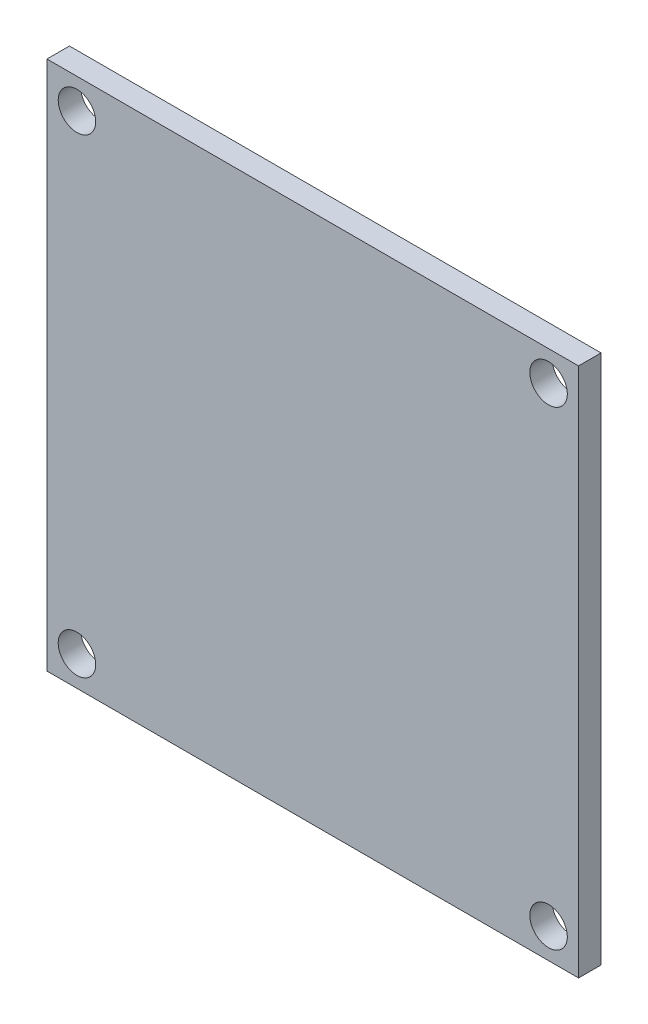
SolidWorks part; units mm, degrees
ref_plane "前视基准面" through (0, 0, 0) normal (0, 0, 1) x (1, 0, 0)
ref_plane "上视基准面" through (0, 0, 0) normal (0, 1, 0) x (1, 0, 0)
ref_plane "右视基准面" through (0, 0, 0) normal (1, 0, 0) x (0, 0, -1)
other "Configuration Table"
sketch "草图1" plane through (0, 0, 0) normal (0, 0, 1) x (1, 0, 0)
  line L1 (-35.45, 35.35) -> (35.45, 35.35)
  line L2 (-35.45, 35.35) -> (-35.45, -35.35)
  line L3 (-35.45, -35.35) -> (35.45, -35.35)
  line L4 (35.45, 35.35) -> (35.45, -35.35)
  point P4 (0, 35.35)
  point P5 (35.45, 0)
  dimension "D1" = 70.9
  dimension "D2" = 70.7
extrude "凸台-拉伸1" add sketch "草图1" along normal blind 3
sketch "草图2" plane through (0, 0, 0) normal (0, 0, -1) x (-1, 0, 0)
  line L0 (-35.45, -35.35) -> (-35.45, 35.35) construction
  line L1 (-35.45, 35.35) -> (35.45, 35.35) construction
  line L2 (35.45, -35.35) -> (-35.45, -35.35) construction
  line L3 (35.45, 35.35) -> (35.45, -35.35) construction
  circle A0 centre (-31.45, 31.35) radius 2.5
  circle A1 centre (-31.45, -31.35) radius 2.5
  circle A2 centre (31.45, -31.35) radius 2.5
  circle A3 centre (31.45, 31.35) radius 2.5
  dimension "D1" = 5
  dimension "D2" = 4
  dimension "D3" = 4
  dimension "D4" = 4
  dimension "D5" = 4
extrude "切除-拉伸1" cut sketch "草图2" against normal through all
